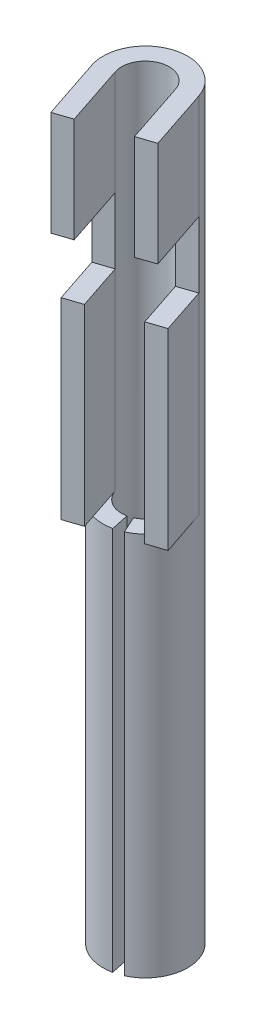
SolidWorks part; units mm, degrees
ref_plane "Front Plane" through (0, 0, 0) normal (0, 0, 1) x (1, 0, 0)
ref_plane "Top Plane" through (0, 0, 0) normal (0, 1, 0) x (1, 0, 0)
ref_plane "Right Plane" through (0, 0, 0) normal (1, 0, 0) x (0, 0, -1)
sketch "Sketch1" plane through (0, 0, 0) normal (0, 1, 0) x (1, 0, 0)
  line L0 (0, 0) -> (0.2886, -0.6361) construction
  line L1 (0.2886, -0.6361) -> (0, 0) construction
  line L2 (0, 0) -> (0.1443, -0.6834) construction
  arc A0 (0.2886, -0.6361) -> (0.1443, -0.6834) centre (0, 0) ccw
  dimension "D1" = 1.397
extrude "Extrude-Thin1" add sketch "Sketch1" along normal blind 6.35 thin thin type one direction reverse wall 0.3048
sketch "Sketch2" plane through (0, 6.35, 0) normal (0, 1, 0) x (1, 0, 0)
  line L0 (0.3179, -0.9544) -> (-0.2207, 0.6627) construction
  line L1 (-0.6627, -0.2207) -> (0.6627, 0.2207) construction
  line L2 (0.0813, -0.3852) -> (0.1443, -0.6834) construction
  line L3 (-0.6627, -0.2207) -> (-0.4089, -0.9827)
  line L4 (0.6627, 0.2207) -> (0.9165, -0.5413)
  arc A0 (0.6627, 0.2207) -> (-0.6627, -0.2207) centre (0, 0) ccw
  arc A1 (0.2886, -0.6361) -> (0.1443, -0.6834) centre (0, 0) ccw construction
  dimension "D1" = 6.5
  dimension "D2" = 0.762
extrude "Extrude-Thin2" add sketch "Sketch2" along normal blind 3.175 thin thin type one direction wall 0.3048
sketch "Sketch3" plane through (0, 9.525, 0) normal (0, 1, 0) x (1, 0, 0)
  line L0 (-0.6627, -0.2207) -> (0.6627, 0.2207) construction
  arc A0 (0.6627, 0.2207) -> (-0.6627, -0.2207) centre (0, 0) ccw
extrude "Extrude-Thin3" add sketch "Sketch3" along normal blind 1.0922 thin thin type one direction reverse wall 0.3048
sketch "Sketch4" plane through (0, 10.6172, 0) normal (0, 1, 0) x (1, 0, 0)
  line L0 (-0.6627, -0.2207) -> (-0.3243, -1.2367)
  line L1 (0.6627, 0.2207) -> (1.0011, -0.7953)
  line L2 (-0.3735, -0.1244) -> (-0.6627, -0.2207) construction
  arc A0 (0.6627, 0.2207) -> (-0.6627, -0.2207) centre (0, 0) ccw
  dimension "D1" = 1.016
extrude "Extrude-Thin4" add sketch "Sketch4" along normal blind 1.7272 thin thin type one direction wall 0.3048
